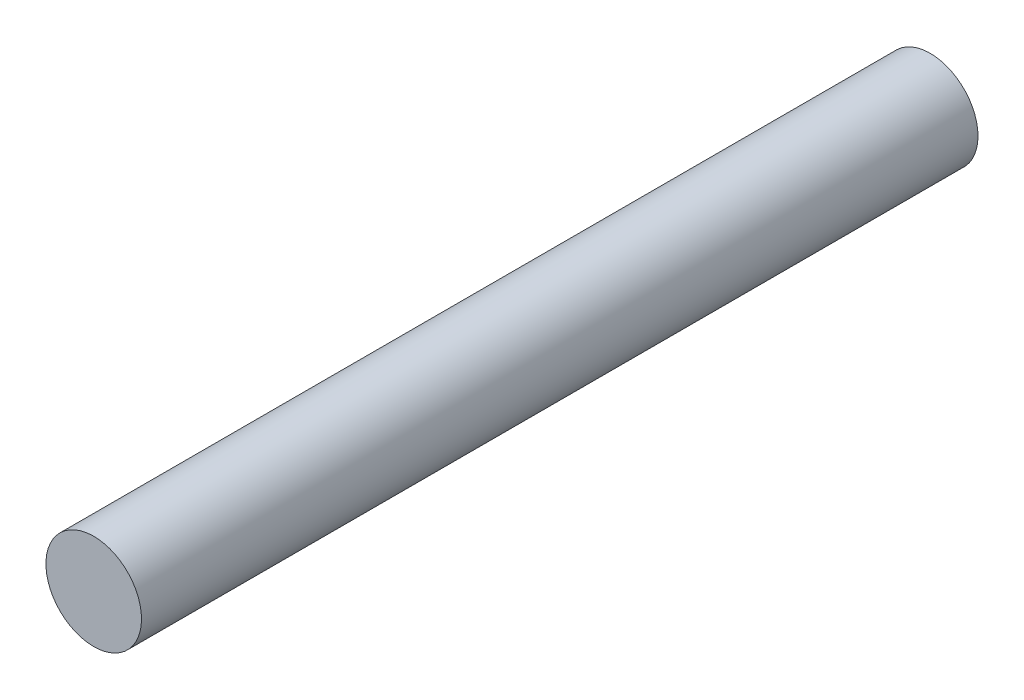
SolidWorks part; units mm, degrees
ref_plane "Front Plane" through (0, 0, 0) normal (0, 0, 1) x (1, 0, 0)
ref_plane "Top Plane" through (0, 0, 0) normal (0, 1, 0) x (1, 0, 0)
ref_plane "Right Plane" through (0, 0, 0) normal (1, 0, 0) x (0, 0, -1)
sketch "Sketch1" plane through (0, 0, 0) normal (0, 0, 1) x (1, 0, 0)
  circle A0 centre (67.255, 46.7976) radius 4
extrude "Boss-Extrude2" add sketch "Sketch1" along normal blind 70
